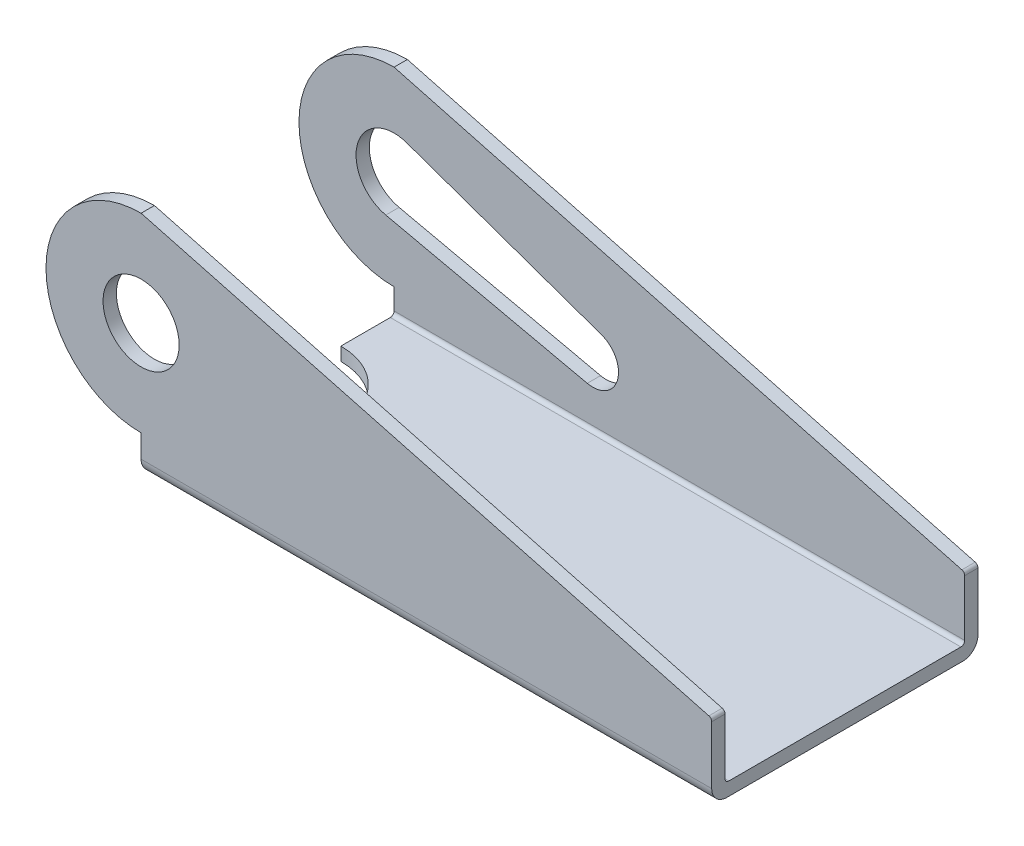
SolidWorks part; units mm, degrees
ref_plane "Front Plane" through (0, 0, 0) normal (0, 0, 1) x (1, 0, 0)
ref_plane "Top Plane" through (0, 0, 0) normal (0, 1, 0) x (1, 0, 0)
ref_plane "Right Plane" through (0, 0, 0) normal (1, 0, 0) x (0, 0, -1)
sketch "Sketch2" plane through (0, 0, 0) normal (0, 0, 1) x (1, 0, 0)
  line L0 (-19.05, 0) -> (19.05, 0)
  line L1 (19.05, 0) -> (19.05, 5.08)
  line L2 (19.05, 5.08) -> (-19.05, 15.24)
  line L3 (-19.05, 0) -> (-19.05, 2.54)
  line L4 (55, 0) -> (-55, 0) construction
  arc A0 (-19.05, 2.54) -> (-19.05, 15.24) centre (-19.05, 8.89) cw
  point P8 (0, 0)
  dimension "D1" = 38.1
  dimension "D2" = 5.08
  dimension "D3" = 15.24
  dimension "D4" = 6.35
extrude "Extruded Boss Front Plane Wing" add sketch "Sketch2" along normal blind 8.89 and the other way blind 8.89
sketch "Sketch3" plane through (0, 0, 0) normal (1, 0, 0) x (0, 0, -1)
  line L0 (-8.001, 15.24) -> (-8.001, 0.889)
  line L1 (8.89, 15.24) -> (-8.89, 15.24) construction
  line L2 (-8.001, 0.889) -> (8.001, 0.889)
  line L3 (8.001, 0.889) -> (8.001, 15.24)
  line L4 (8.001, 15.24) -> (-8.001, 15.24)
  line L5 (-8.89, 0) -> (-8.89, 5.08) construction
  line L6 (8.89, 0) -> (8.89, 5.08) construction
  line L7 (55, 0) -> (-55, 0) construction
  dimension "D1" = 0.889
  dimension "D2" = 0.889
  dimension "D3" = 0.889
extrude "Extruded Cut Right Plane Wing" cut sketch "Sketch3" against normal through all and the other way through all
hole_wizard "2X 0.2D Holes" positions "Sketch4" profile "Sketch5" hole size "1/16" standard "ANSI Inch" end condition through all
sketch "Sketch4" plane through (0, 0, 8.89) normal (0, 0, 1) x (1, 0, 0)
  point P0 (-19.05, 8.89)
sketch "Sketch5" plane through (-19.05, 8.89, 8.89) normal (1, 0, 0) x (0, -1, 0)
  line L0 (0, 0) -> (0, 17.78)
  line L1 (0, 17.78) -> (2.54, 17.78)
  line L2 (2.54, 17.78) -> (2.54, 0)
  line L5 (2.54, 0) -> (0, 0)
  line L11 (0, -6.35) -> (0, 107.95) construction
  dimension "Thru Hole Dia." = 5.08
  dimension "Thru Hole Depth" = 17.78
hole_wizard "0.35D Hole" positions "Sketch6" profile "Sketch7" hole size "1/16" standard "ANSI Inch" end condition through all
sketch "Sketch6" plane through (0, 0.889, 0) normal (0, 1, 0) x (1, 0, 0)
  line L0 (-19.05, 8.001) -> (-19.05, -8.001) construction
  point P0 (-19.05, 0)
sketch "Sketch7" plane through (-19.05, 0.889, 0) normal (1, 0, 0) x (0, 0, 1)
  line L0 (0, 0) -> (0, 0.889)
  line L1 (0, 0.889) -> (4.445, 0.889)
  line L2 (4.445, 0.889) -> (4.445, 0)
  line L5 (4.445, 0) -> (0, 0)
  line L11 (0, -6.35) -> (0, 107.95) construction
  dimension "Thru Hole Dia." = 8.89
  dimension "Thru Hole Depth" = 0.889
hole_wizard "0.135D Hole" positions "Sketch12" profile "Sketch13" hole size "1/16" standard "ANSI Inch"
sketch "Sketch12" plane through (0, 0, -8.001) normal (0, 0, 1) x (1, 0, 0)
  line L0 (19.05, 0) -> (19.05, 5.08) construction
  line L1 (9.779, 0) -> (-9.779, 0) construction
  point P0 (-5.7785, 5.08)
  dimension "D1" = 24.8285
  dimension "D2" = 5.08
sketch "Sketch13" plane through (-5.7785, 5.08, -8.001) normal (1, 0, 0) x (0, -1, 0)
  line L0 (0, 0) -> (0, 0.889)
  line L1 (0, 0.889) -> (1.7145, 0.889)
  line L2 (1.7145, 0.889) -> (1.7145, 0)
  line L5 (1.7145, 0) -> (0, 0)
  line L11 (0, -6.35) -> (0, 107.95) construction
  dimension "Thru Hole Dia." = 3.429
  dimension "Thru Hole Depth" = 0.889
sketch "Sketch14" plane through (0, 0, -8.001) normal (0, 0, 1) x (1, 0, 0)
  line L0 (-19.6037, 6.4111) -> (-6.1522, 3.4067)
  line L1 (-6.1522, 3.4067) -> (-5.2077, 6.6967)
  line L2 (-5.2077, 6.6967) -> (-18.2044, 11.2851)
  line L3 (-18.2044, 11.2851) -> (-19.6037, 6.4111)
  circle A0 centre (-19.05, 8.89) radius 2.54 construction
  circle A1 centre (-5.7785, 5.08) radius 1.7145 construction
extrude "0.2D-0.135D Hole Connecting Cut" cut sketch "Sketch14" against normal through all
fillet "Inner Connecting Fillet" radius 0.254 4 edges at (0, 0.889, 8.001) (0, 0.889, -8.001) (19.05, 5.08, 8.4455) (19.05, 5.08, -8.4455)
fillet "Outter Connecting Fillet" radius 1.016 2 edges at (0, 0, 8.89) (0, 0, -8.89)
